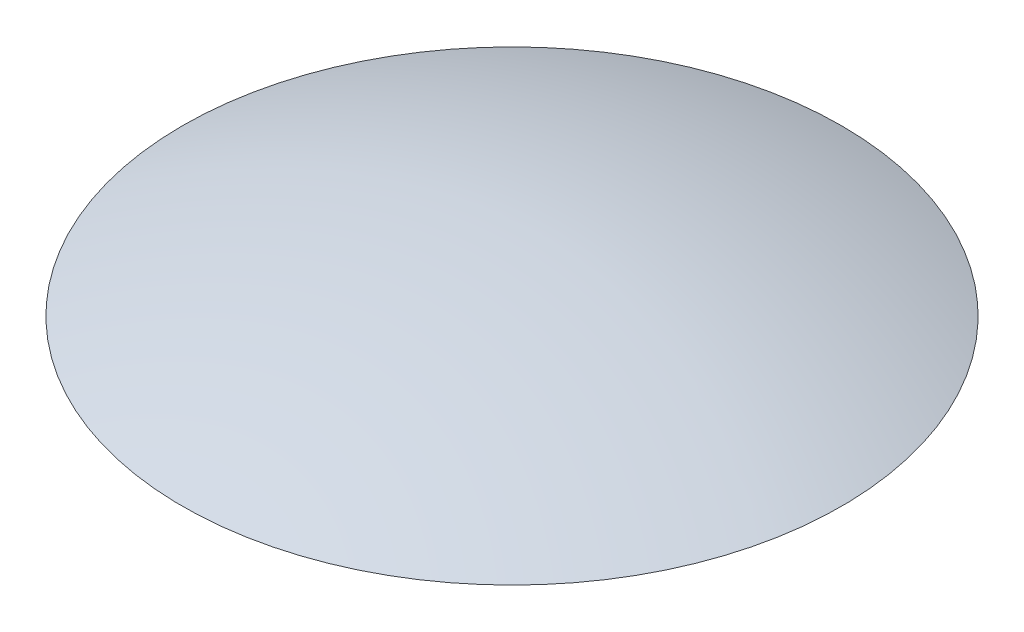
SolidWorks part; units mm, degrees
material "Cast Stainless Steel"
ref_plane "Front Plane" through (0, 0, 0) normal (0, 0, 1) x (1, 0, 0)
ref_plane "Top Plane" through (0, 0, 0) normal (0, 1, 0) x (1, 0, 0)
ref_plane "Right Plane" through (0, 0, 0) normal (1, 0, 0) x (0, 0, -1)
sketch "Sketch1" plane through (0, 0, 0) normal (0, 1, 0) x (1, 0, 0)
  circle A0 centre (0, 0) radius 2.5
  circle A1 centre (0, 0) radius 3
  dimension "D1" = 5
  dimension "D2" = 0.5
extrude "Boss-Extrude1" add sketch "Sketch1" along normal blind 1
sketch "Sketch4" plane through (0, 0, 0) normal (0, 0, 1) x (1, 0, 0)
  line L0 (0, 1) -> (-5, 1)
  line L1 (3, 1) -> (-3, 1) construction
  line L3 (0, 0) -> (0, 1) construction
  line L4 (0, 2) -> (0, 1)
  line L5 (0, 2) -> (0, 2.9188) construction
  spline S0 degree 2 poles (-5, 1) (-2.5, 2) (0, 2) knots 0 0 0 0.5 0.5 0.5
  dimension "D1" = 5
revolve "Revolve3" add sketch "Sketch4" angle 360 about L3
